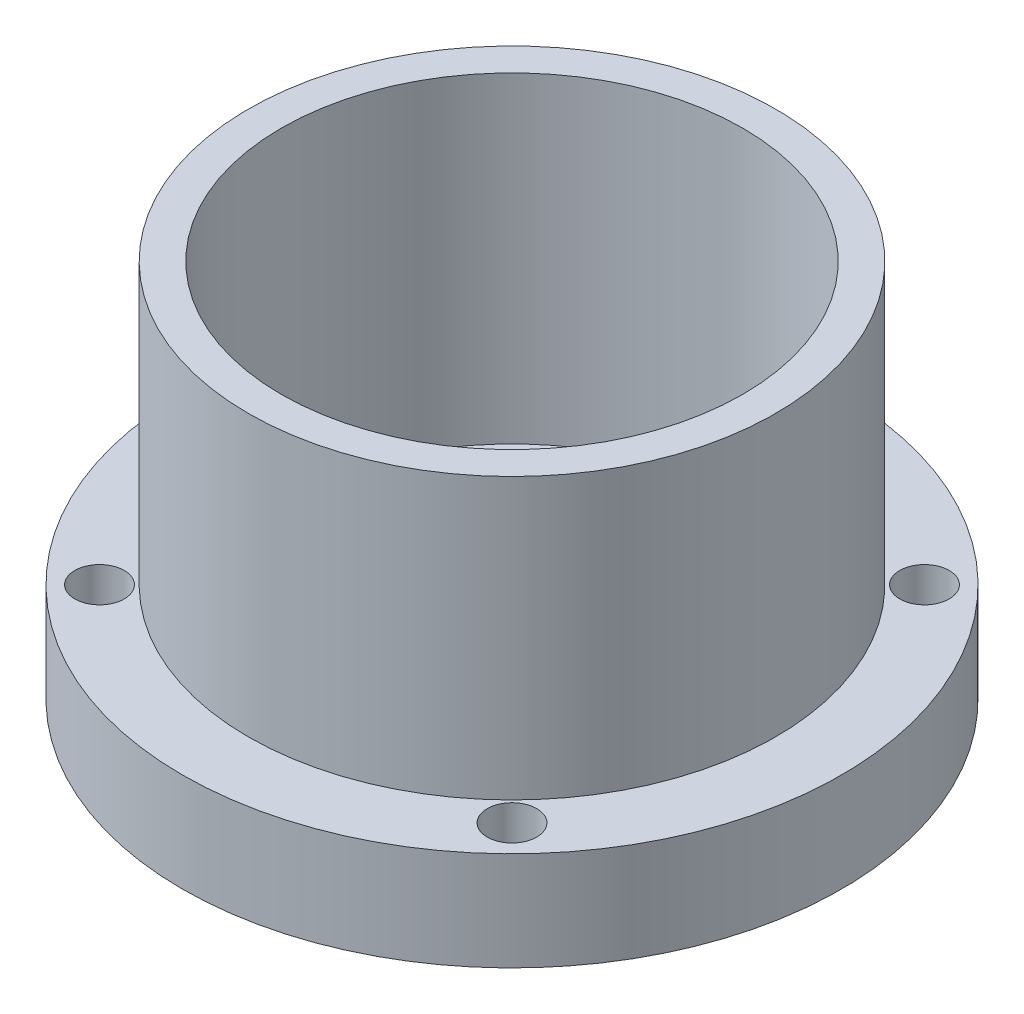
SolidWorks part; units mm, degrees
other "Bearing Cartridge"
other "Bearing Cartridge Left"
ref_plane "Front Plane" through (0, 0, 0) normal (0, 0, 1) x (1, 0, 0)
ref_plane "Top Plane" through (0, 0, 0) normal (0, 1, 0) x (1, 0, 0)
ref_plane "Right Plane" through (0, 0, 0) normal (1, 0, 0) x (0, 0, -1)
sketch3d "Cartridge barrel sketch datum points"
  point P0 (-19.0092, -237.5, -53.2449)
  point P1 (-9.0092, -237.5, -53.2449)
  point P2 (-19.0092, -237.5, -63.2449)
ref_plane "Cartridge barrel sketch plane" through (0, -237.5, 0) normal (0, 1, 0) x (1, 0, 0)
sketch "Cartridge barrel sketch" plane through (0, -237.5, 0) normal (0, 1, 0) x (1, 0, 0)
  circle A0 centre (-19.0092, 53.2449) radius 16
extrude "Cartridge barrel" add sketch "Cartridge barrel sketch" along normal blind 17 separate body
sketch3d "Six millimetre flange sketch datum points"
  point P0 (-19.0092, -220.5, -53.2449)
  point P1 (-9.0092, -220.5, -53.2449)
  point P2 (-19.0092, -220.5, -63.2449)
ref_plane "Six millimetre flange sketch plane" through (0, -220.5, 0) normal (0, 1, 0) x (1, 0, 0)
sketch "Six millimetre flange sketch" plane through (0, -220.5, 0) normal (0, 1, 0) x (1, 0, 0)
  circle A0 centre (-19.0092, 53.2449) radius 20
extrude "Six millimetre flange" add sketch "Six millimetre flange sketch" along normal blind 6
sketch3d "Bearing bore sketch datum points"
  point P0 (-19.0092, -237.6, -53.2449)
  point P1 (-9.0092, -237.6, -53.2449)
  point P2 (-19.0092, -237.6, -63.2449)
ref_plane "Bearing bore sketch plane" through (0, -237.6, 0) normal (0, 1, 0) x (1, 0, 0)
sketch "Bearing bore sketch" plane through (0, -237.6, 0) normal (0, 1, 0) x (1, 0, 0)
  circle A0 centre (-19.0092, 53.2449) radius 14
extrude "Bearing bore" cut sketch "Bearing bore sketch" along normal blind 19.6
sketch3d "Outer race shoulder exit sketch datum points"
  point P0 (-19.0092, -218, -53.2449)
  point P1 (-9.0092, -218, -53.2449)
  point P2 (-19.0092, -218, -63.2449)
ref_plane "Outer race shoulder exit sketch plane" through (0, -218, 0) normal (0, 1, 0) x (1, 0, 0)
sketch "Outer race shoulder exit sketch" plane through (0, -218, 0) normal (0, 1, 0) x (1, 0, 0)
  circle A0 centre (-19.0092, 53.2449) radius 13
extrude "Outer race shoulder exit" cut sketch "Outer race shoulder exit sketch" along normal blind 3.6
sketch3d "M3 tapped hole pattern sketch datum points"
  point P0 (-19.0092, -220.6, -53.2449)
  point P1 (-9.0092, -220.6, -53.2449)
  point P2 (-19.0092, -220.6, -63.2449)
ref_plane "M3 tapped hole pattern sketch plane" through (0, -220.6, 0) normal (0, 1, 0) x (1, 0, 0)
sketch "M3 tapped hole pattern sketch" plane through (0, -220.6, 0) normal (0, 1, 0) x (1, 0, 0)
  circle A0 centre (-6.4934, 40.7291) radius 1.5
  circle A1 centre (-31.525, 40.7291) radius 1.5
  circle A2 centre (-31.525, 65.7607) radius 1.5
  circle A3 centre (-6.4934, 65.7607) radius 1.5
extrude "M3 tapped hole pattern" cut sketch "M3 tapped hole pattern sketch" along normal blind 6.2
sketch3d "Mirror1 profile datum points"
  point P0 (0, 0, 0)
  point P1 (10, 0, 0)
  point P2 (0, 0, 10)
ref_plane "Mirror1 profile plane" through (0, 0, 0) normal (0, -1, 0) x (-1, 0, 0)
mirror "Mirror1" about plane through (0, 0, 0) normal (0, -1, 0) of bodies 105
delete or keep bodies "Remove1" type delete bodies bodies 105
